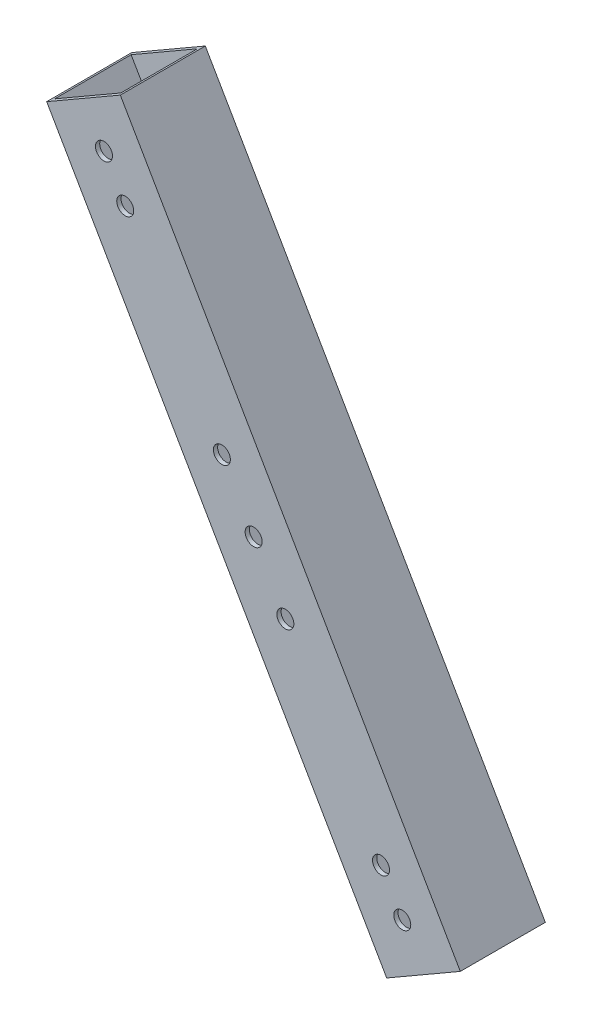
SolidWorks part; units mm, degrees
ref_plane "前视基准面" through (0, 0, 0) normal (0, 0, 1) x (1, 0, 0)
ref_plane "上视基准面" through (0, 0, 0) normal (0, 1, 0) x (1, 0, 0)
ref_plane "右视基准面" through (0, 0, 0) normal (1, 0, 0) x (0, 0, -1)
sketch "草图1" plane through (0, 0, 0) normal (0, 0, 1) x (1, 0, 0)
  line L0 (-48.7271, 63.8479) -> (31.2729, -74.7162)
  line L1 (31.2729, -74.7162) -> (48.5934, -64.7162)
  line L2 (48.5934, -64.7162) -> (-31.4066, 73.8479)
  line L3 (-31.4066, 73.8479) -> (-48.7271, 63.8479)
  circle A0 centre (-35.2464, 60.4985) radius 2
  circle A1 centre (-30.2464, 51.8383) radius 2
  circle A2 centre (-7.5019, 12.5283) radius 2
  circle A3 centre (-0.0377, -0.4828) radius 2
  circle A4 centre (7.4264, -13.4939) radius 2
  circle A5 centre (29.9331, -52.3957) radius 2
  circle A6 centre (34.9331, -61.0559) radius 2
extrude "凸台-拉伸1" add sketch "草图1" along normal blind 20
sketch "草图2" plane through (-39.8287, 68.9854, 0) normal (-0.5, 0.866, 0) x (0.866, 0.5, 0)
  line L0 (-0.275, 0) -> (-0.275, -20) construction
  line L1 (9.725, 0) -> (-10.275, 0) construction
  line L2 (9.725, -20) -> (-10.275, -20) construction
  line L4 (-9.275, -1) -> (8.725, -1)
  line L5 (-9.275, -1) -> (-9.275, -19)
  line L6 (-9.275, -19) -> (8.725, -19)
  line L7 (8.725, -1) -> (8.725, -19)
  line L8 (-0.275, -19) -> (-0.275, -1) construction
  line L9 (-9.275, -10) -> (8.725, -10) construction
  point P6 (-0.275, -10)
  dimension "D1" = 18
  dimension "D2" = 18
extrude "切除-拉伸1" cut sketch "草图2" against normal through all
